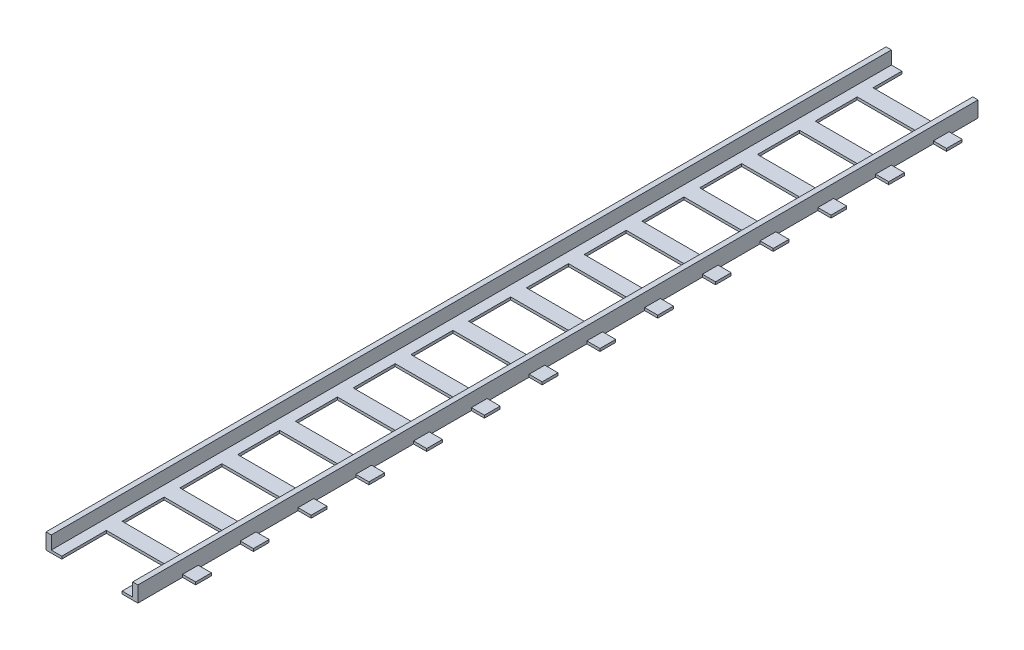
SolidWorks part; units mm, degrees
ref_plane "Front Plane" through (0, 0, 0) normal (0, 0, 1) x (1, 0, 0)
ref_plane "Top Plane" through (0, 0, 0) normal (0, 1, 0) x (1, 0, 0)
ref_plane "Right Plane" through (0, 0, 0) normal (1, 0, 0) x (0, 0, -1)
sketch "Sketch1" plane through (0, 0, 0) normal (0, 0, 1) x (1, 0, 0)
  line L0 (0, 0) -> (34.1496, 0) construction
  line L1 (0, 0) -> (0, 31.0102) construction
  line L2 (-17.5, 55.0518) -> (-17.5, -17.4086) construction
  line L3 (17.5, 36.4149) -> (17.5, -13.0848) construction
  line L6 (-17.5, 0) -> (-17.5, 6)
  line L7 (-17.5, 6) -> (-15.5, 6)
  line L8 (-15.5, 1) -> (-15.5, 6)
  line L9 (-17.5, 0) -> (-11.5, 0)
  line L10 (17.5, 0) -> (17.5, 6)
  line L11 (-15.5, 1) -> (-11.5, 1)
  line L12 (-11.5, 0) -> (-11.5, 1)
  line L13 (17.5, 6) -> (15.5, 6)
  line L14 (15.5, 1) -> (15.5, 6)
  line L15 (17.5, 0) -> (11.5, 0)
  line L17 (15.5, 1) -> (11.5, 1)
  line L18 (11.5, 0) -> (11.5, 1)
  dimension "D1" = 17.5
  dimension "D2" = 17.5
extrude "Boss-Extrude1" add sketch "Sketch1" along normal blind 320
sketch "Sketch3" plane through (0, 0, 0) normal (0, 1, 0) x (1, 0, 0)
  line L0 (-17.5, -320) -> (-17.5, 0) construction
  line L1 (-22.5, -11) -> (22.5, -11)
  line L2 (-22.5, -11) -> (-22.5, -17)
  line L3 (-22.5, -17) -> (22.5, -17)
  line L4 (22.5, -11) -> (22.5, -17)
  line L5 (17.5, -320) -> (17.5, 0) construction
  line L6 (-11.5, 0) -> (-15.5, 0) construction
  line L8 (-22.5, -33) -> (22.5, -33)
  line L9 (-22.5, -33) -> (-22.5, -39)
  line L10 (-22.5, -39) -> (22.5, -39)
  line L11 (22.5, -33) -> (22.5, -39)
  line L12 (-22.5, -55) -> (22.5, -55)
  line L13 (-22.5, -55) -> (-22.5, -61)
  line L14 (-22.5, -61) -> (22.5, -61)
  line L15 (22.5, -55) -> (22.5, -61)
  line L16 (-22.5, -77) -> (22.5, -77)
  line L17 (-22.5, -77) -> (-22.5, -83)
  line L18 (-22.5, -83) -> (22.5, -83)
  line L19 (22.5, -77) -> (22.5, -83)
  line L20 (-22.5, -99) -> (22.5, -99)
  line L21 (-22.5, -99) -> (-22.5, -105)
  line L22 (-22.5, -105) -> (22.5, -105)
  line L23 (22.5, -99) -> (22.5, -105)
  line L24 (-22.5, -121) -> (22.5, -121)
  line L25 (-22.5, -121) -> (-22.5, -127)
  line L26 (-22.5, -127) -> (22.5, -127)
  line L27 (22.5, -121) -> (22.5, -127)
  line L28 (-22.5, -143) -> (22.5, -143)
  line L29 (-22.5, -143) -> (-22.5, -149)
  line L30 (-22.5, -149) -> (22.5, -149)
  line L31 (22.5, -143) -> (22.5, -149)
  line L32 (-22.5, -165) -> (22.5, -165)
  line L33 (-22.5, -165) -> (-22.5, -171)
  line L34 (-22.5, -171) -> (22.5, -171)
  line L35 (22.5, -165) -> (22.5, -171)
  line L36 (-22.5, -187) -> (22.5, -187)
  line L37 (-22.5, -187) -> (-22.5, -193)
  line L38 (-22.5, -193) -> (22.5, -193)
  line L39 (22.5, -187) -> (22.5, -193)
  line L40 (-22.5, -209) -> (22.5, -209)
  line L41 (-22.5, -209) -> (-22.5, -215)
  line L42 (-22.5, -215) -> (22.5, -215)
  line L43 (22.5, -209) -> (22.5, -215)
  line L44 (-22.5, -231) -> (22.5, -231)
  line L45 (-22.5, -231) -> (-22.5, -237)
  line L46 (-22.5, -237) -> (22.5, -237)
  line L47 (22.5, -231) -> (22.5, -237)
  line L48 (-22.5, -253) -> (22.5, -253)
  line L49 (-22.5, -253) -> (-22.5, -259)
  line L50 (-22.5, -259) -> (22.5, -259)
  line L51 (22.5, -253) -> (22.5, -259)
  line L52 (-22.5, -275) -> (22.5, -275)
  line L53 (-22.5, -275) -> (-22.5, -281)
  line L54 (-22.5, -281) -> (22.5, -281)
  line L55 (22.5, -275) -> (22.5, -281)
  line L56 (-22.5, -297) -> (22.5, -297)
  line L57 (-22.5, -297) -> (-22.5, -303)
  line L58 (-22.5, -303) -> (22.5, -303)
  line L59 (22.5, -297) -> (22.5, -303)
  dimension "D1" = 5
  dimension "D2" = 5
  dimension "D3" = 6
  dimension "D4" = 11
  dimension "D5" = 14
extrude "Boss-Extrude2" add sketch "Sketch3" along normal blind 1
